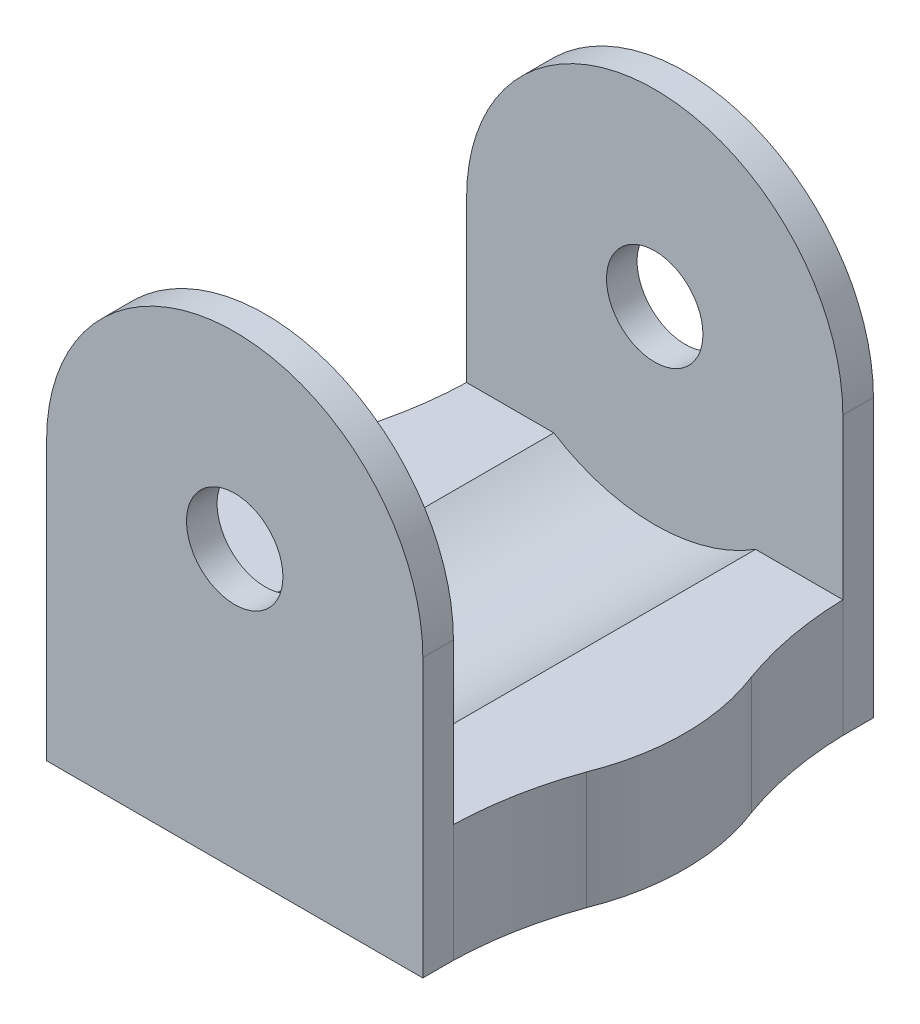
SolidWorks part; units mm, degrees
ref_plane "Front Plane" through (0, 0, 0) normal (0, 0, 1) x (1, 0, 0)
ref_plane "Top Plane" through (0, 0, 0) normal (0, 1, 0) x (1, 0, 0)
ref_plane "Right Plane" through (0, 0, 0) normal (1, 0, 0) x (0, 0, -1)
sketch "Sketch1" plane through (0, 0, 0) normal (0, 1, 0) x (1, 0, 0)
  circle A0 centre (0, 0) radius 41.5
  circle A1 centre (0, 0) radius 47.8
  dimension "D1" = 83
  dimension "D2" = 6.3
extrude "Cap base" add sketch "Sketch1" along normal blind 15
sketch "Sketch2" plane through (0, 15, 0) normal (0, 1, 0) x (1, 0, 0)
  circle A0 centre (0, 0) radius 47.8 construction
  circle A1 centre (0, 0) radius 47.8
extrude "Cap top" add sketch "Sketch2" along normal blind 10
sketch "Sketch3" plane through (0, 0, 0) normal (0, 0, 1) x (1, 0, 0)
  line L0 (-41.5, 15) -> (41.5, 15) construction
  line L1 (-40, 59) -> (-40, 0)
  line L2 (-47.8, 0) -> (47.8, 0) construction
  line L3 (40, 59) -> (40, 0)
  line L4 (40, 0) -> (-40, 0)
  arc A0 (40, 59) -> (-40, 59) centre (0, 59) ccw
  dimension "D1" = 80
  dimension "D2" = 44
  dimension "D3" = 59
extrude "Sides" add sketch "Sketch3" along normal blind 6.5 from offset 41.4
sketch "Sketch4" plane through (0, 25, 0) normal (0, 1, 0) x (1, 0, 0)
  line L1 (40, -41.4) -> (-40, -41.4) construction
  line L2 (0, -55) -> (0, 55) construction
  line L3 (40, -41.4) -> (23.8931, -41.4)
  line L4 (-23.8931, -41.4) -> (-40, -41.4)
  arc A0 (-40, -41.4) -> (-45.1045, -15.8247) centre (-116.4461, -43.3607) ccw
  arc A1 (23.8931, -41.4) -> (-23.8931, -41.4) centre (0, 0) ccw construction
  arc A2 (40, -41.4) -> (45.1045, -15.8247) centre (116.4461, -43.3607) cw
  arc A3 (23.8931, -41.4) -> (45.1045, -15.8247) centre (0, 0) ccw
  arc A4 (-45.1045, -15.8247) -> (-23.8931, -41.4) centre (0, 0) ccw
  arc M1 (23.8931, -41.4) -> (-23.8931, -41.4) centre (0, 0) ccw
  dimension "D1" = 25.5753
  dimension "D2" = 76.4712
extrude "Sides to cap" add sketch "Sketch4" against normal blind 25 contours A0 L4 M1 | L3 A2 M1
mirror "Mirror1" about plane through (0, 0, 0) normal (0, 0, 1) of "Sides to cap"
mirror "Mirror sides" about plane through (0, 0, 0) normal (0, 0, 1) of "Sides"
sketch "Sketch5" plane through (0, 0, 41.4) normal (0, 0, -1) x (-1, 0, 0)
  circle A0 centre (0, 59) radius 40.2
  dimension "D1" = 80.4
extrude "Tracks for housing" cut sketch "Sketch5" along normal blind 45
mirror "Mirror tracks" about plane through (0, 0, 0) normal (0, 0, 1) of "Tracks for housing"
sketch "Sketch6" plane through (0, 0, 47.9) normal (0, 0, 1) x (1, 0, 0)
  circle A0 centre (0, 59) radius 10.25
  dimension "D1" = 20.5
extrude "Hole for gear shafts" cut sketch "Sketch6" against normal through all
equation "\"D2@Sketch3\"=\"D1@Sketch3\"/2+4"
equation "\"D3@Sketch3\"=\"D2@Sketch3\"+15"
